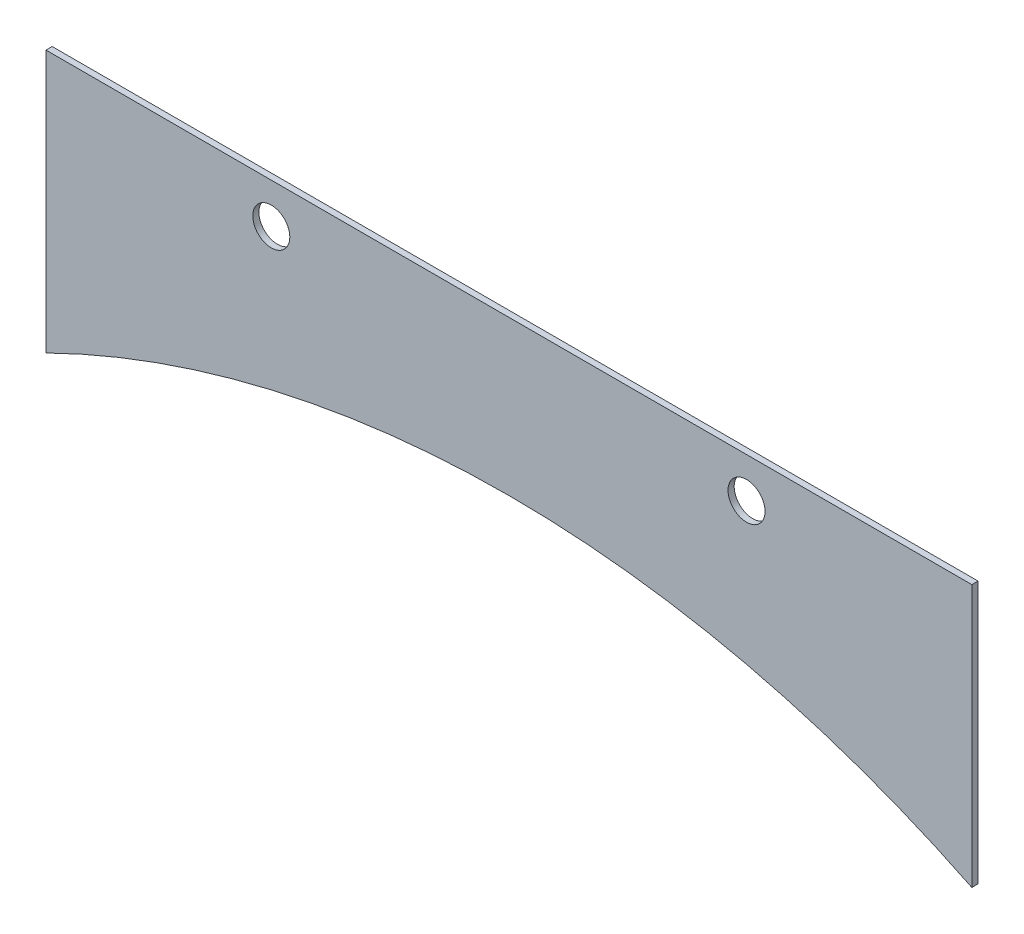
SolidWorks part; units mm, degrees
ref_plane "Alzado" through (0, 0, 0) normal (0, 0, 1) x (1, 0, 0)
ref_plane "Planta" through (0, 0, 0) normal (0, 1, 0) x (1, 0, 0)
ref_plane "Vista lateral" through (0, 0, 0) normal (1, 0, 0) x (0, 0, -1)
sketch "Croquis1" plane through (0, 0, 0) normal (0, 0, 1) x (1, 0, 0)
  line L0 (-150, 0) -> (-150, 85)
  line L3 (-150, 85) -> (150, 85)
  line L4 (150, 85) -> (150, 0)
  arc A1 (150, 0) -> (-150, 0) centre (0, -303.9286) ccw
  point P5 (0, 35)
  dimension "D1" = 85
  dimension "D2" = 150
  dimension "D4" = 50
  dimension "D3" = 300
extrude "Saliente-Extruir1" add sketch "Croquis1" along normal blind 2
sketch "Croquis2" plane through (0, 0, 2) normal (0, 0, 1) x (1, 0, 0)
  line L0 (-150, 85) -> (-150, 0) construction
  line L1 (150, 0) -> (150, 85) construction
  line L2 (150, 85) -> (-150, 85) construction
  circle A0 centre (-77, 72) radius 6
  circle A1 centre (77, 72) radius 6
  dimension "D1" = 12
  dimension "D2" = 12
  dimension "D3" = 73
  dimension "D4" = 73
  dimension "D5" = 13
  dimension "D6" = 13
extrude "Cortar-Extruir1" cut sketch "Croquis2" against normal through all
